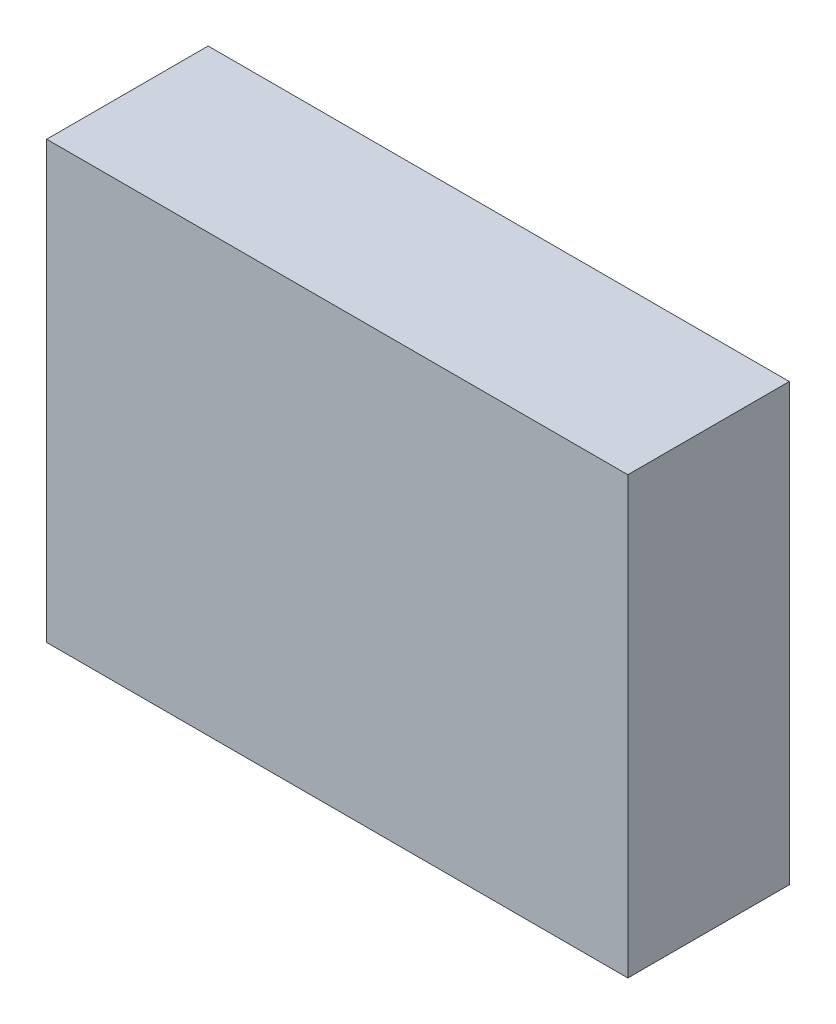
SolidWorks part; units mm, degrees
ref_plane "Front Plane" through (0, 0, 0) normal (0, 0, 1) x (1, 0, 0)
ref_plane "Top Plane" through (0, 0, 0) normal (0, 1, 0) x (1, 0, 0)
ref_plane "Right Plane" through (0, 0, 0) normal (1, 0, 0) x (0, 0, -1)
sketch "Sketch1" plane through (0, 0, 0) normal (0, 0, 1) x (1, 0, 0)
  line L1 (0, 0) -> (91.44, 0)
  line L2 (0, 0) -> (0, 68.58)
  line L3 (0, 68.58) -> (91.44, 68.58)
  line L4 (91.44, 0) -> (91.44, 68.58)
  dimension "D1" = 91.44
  dimension "D2" = 68.58
extrude "Boss-Extrude1" add sketch "Sketch1" along normal blind 25.4
